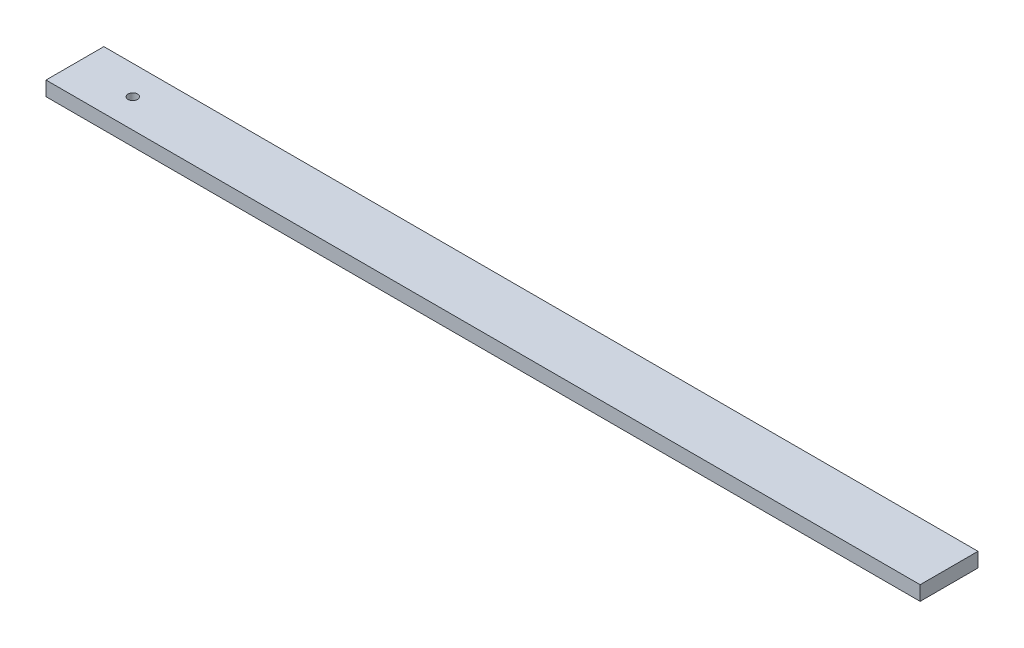
SolidWorks part; units mm, degrees
ref_plane "Front Plane" through (0, 0, 0) normal (0, 0, 1) x (1, 0, 0)
ref_plane "Top Plane" through (0, 0, 0) normal (0, 1, 0) x (1, 0, 0)
ref_plane "Right Plane" through (0, 0, 0) normal (1, 0, 0) x (0, 0, -1)
sketch "Sketch2" plane through (0, 0, 0) normal (0, 1, 0) x (1, 0, 0)
  line L0 (0, 12.7) -> (364.7, 12.7)
  line L1 (0, 0) -> (383.75, 0)
  line L2 (0, 0) -> (0, 25.4)
  line L3 (0, 25.4) -> (383.75, 25.4)
  line L4 (383.75, 0) -> (383.75, 25.4)
  line L5 (364.7, 12.7) -> (364.7, 21.082)
  line L6 (364.7, 12.7) -> (364.7, 4.318)
  dimension "D1" = 383.75
  dimension "D2" = 25.4
  dimension "D3" = 19.05
extrude "Boss-Extrude1" add sketch "Sketch2" along normal blind 6.35
sketch "Sketch3" plane through (0, 6.35, 0) normal (0, 1, 0) x (1, 0, 0)
  line L0 (0, 25.4) -> (0, 12.7)
  line L1 (0, 25.4) -> (383.75, 25.4) construction
  line L2 (0, 0) -> (0, 25.4) construction
  line L3 (0, 12.7) -> (25.4, 12.7)
  circle A1 centre (25.4, 12.7) radius 2.0828
  dimension "D1" = 25.4
  dimension "D2" = 12.7
extrude "Cut-Extrude1" cut sketch "Sketch3" against normal blind 6.35
